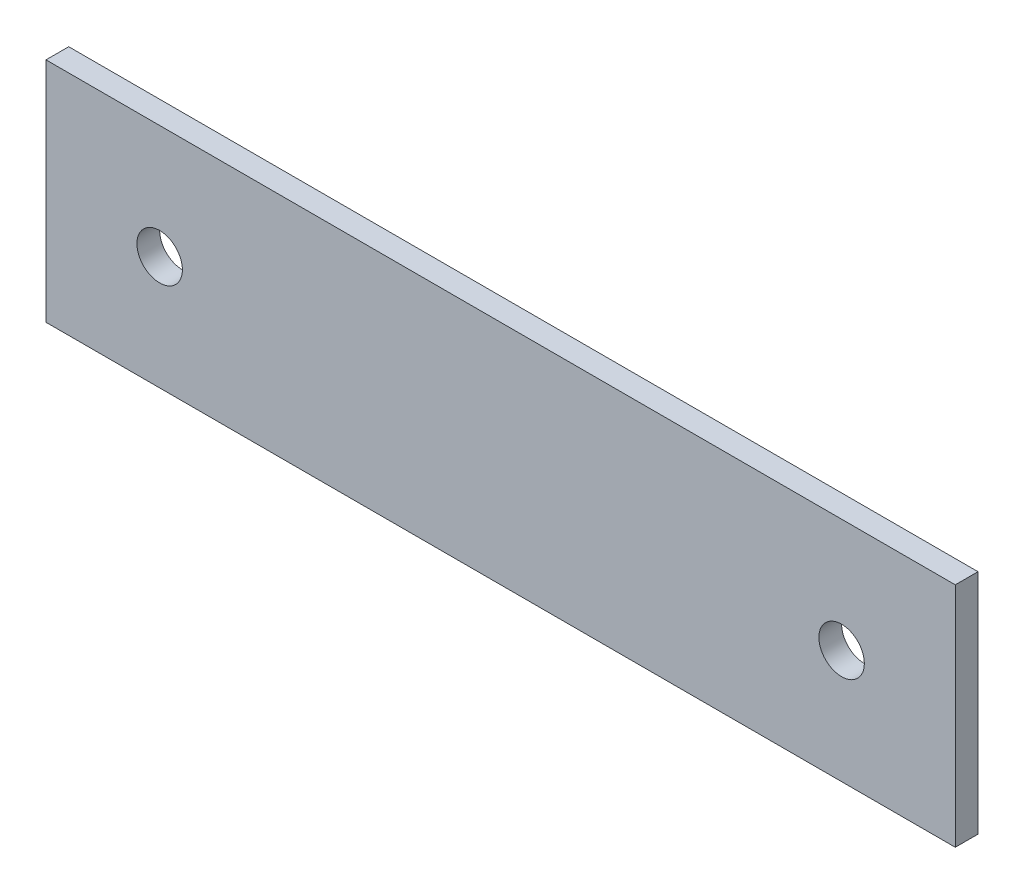
SolidWorks part; units mm, degrees
ref_plane "Front Plane" through (0, 0, 0) normal (0, 0, 1) x (1, 0, 0)
ref_plane "Top Plane" through (0, 0, 0) normal (0, 1, 0) x (1, 0, 0)
ref_plane "Right Plane" through (0, 0, 0) normal (1, 0, 0) x (0, 0, -1)
sketch "Sketch1" plane through (0, 0, 0) normal (0, 0, 1) x (1, 0, 0)
  line L1 (-40, 10) -> (40, 10)
  line L2 (-40, 10) -> (-40, -10)
  line L3 (-40, -10) -> (40, -10)
  line L4 (40, 10) -> (40, -10)
  line L5 (-40, 10) -> (40, -10) construction
  line L6 (-40, -10) -> (40, 10) construction
  point P0 (0, 0)
  dimension "D1" = 80
  dimension "D2" = 20
extrude "Boss-Extrude1" add sketch "Sketch1" along normal blind 2
sketch "Sketch3" plane through (0, 0, 2) normal (0, 0, 1) x (1, 0, 0)
  line L0 (40, -10) -> (40, 10) construction
  line L1 (-40, -10) -> (40, -10) construction
  line L2 (-40, 10) -> (-40, -10) construction
  circle A0 centre (-30, 0) radius 2
  circle A1 centre (30, 0) radius 2
  dimension "D1" = 4
  dimension "D2" = 4
  dimension "D3" = 10
  dimension "D4" = 10
  dimension "D5" = 10
  dimension "D6" = 10
extrude "Cut-Extrude1" cut sketch "Sketch3" against normal blind 2
